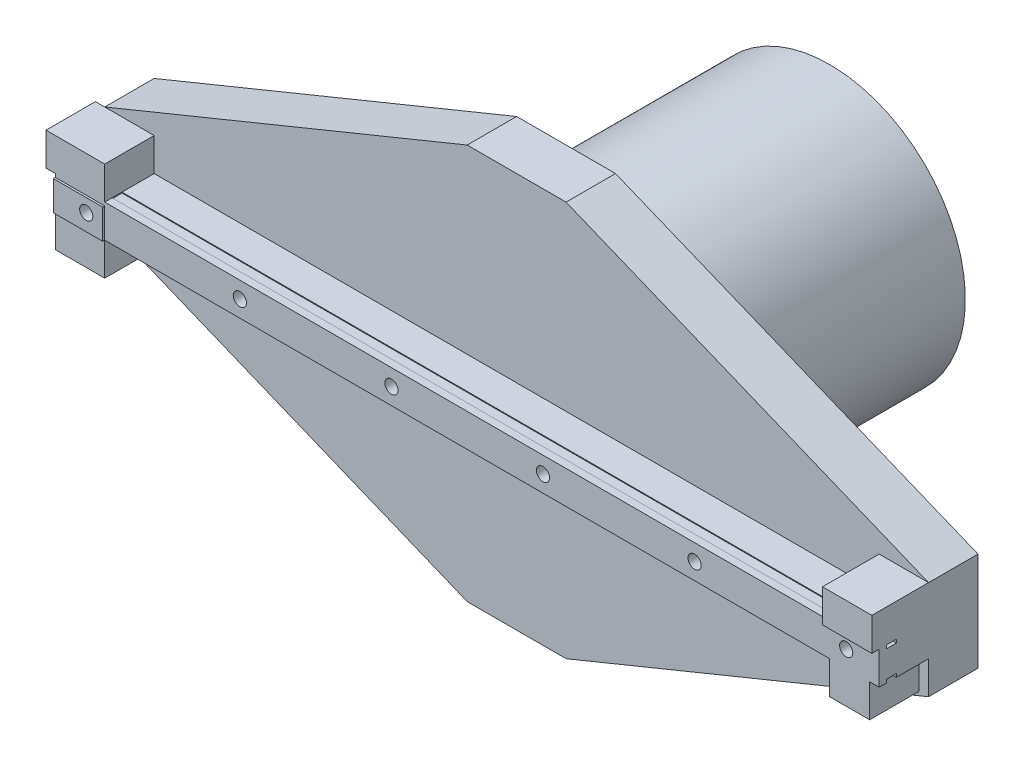
SolidWorks part; units mm, degrees
ref_plane "前视基准面" through (0, 0, 0) normal (0, 0, 1) x (1, 0, 0)
ref_plane "上视基准面" through (0, 0, 0) normal (0, 1, 0) x (1, 0, 0)
ref_plane "右视基准面" through (0, 0, 0) normal (1, 0, 0) x (0, 0, -1)
ref_plane "基准面4" through (0, -5, 0) normal (0, -1, 0) x (1, 0, 0)
sketch "草图1" plane through (0, -5, 0) normal (0, -1, 0) x (1, 0, 0)
  line L0 (-125, 95) -> (-110, 95)
  line L1 (-110, 95) -> (-110, 110.6067)
  line L2 (-110, 110.6067) -> (-125, 110.6067)
  line L3 (-125, 110.6067) -> (-125, 95)
  dimension "D1" = 15.6067
extrude "凸台-拉伸1" add sketch "草图1" against normal blind 9
sketch "草图2" plane through (-110, 0, 0) normal (1, 0, 0) x (0, 0, -1)
  line L0 (-95, 4.7491) -> (-95, -5)
  line L1 (-95, -5) -> (-104.75, -5)
  line L2 (-104.75, -5) -> (-104.75, -4)
  line L3 (-104.75, -4) -> (-107.75, -4)
  line L4 (-107.75, -4) -> (-107.75, -5)
  line L5 (-107.75, -5) -> (-110, -5)
  line L6 (-110, -5) -> (-110, 4.7491)
  line L7 (-110, 4.7491) -> (-95, 4.7491)
  dimension "D1" = 9.7491
extrude "凸台-拉伸2" add sketch "草图2" along normal blind 235
sketch "草图3" plane through (0, 4, 0) normal (0, 1, 0) x (-1, 0, 0)
  line L0 (125, 95) -> (-125, 95)
  line L1 (-125, 95) -> (-125, 110)
  line L2 (-125, 110) -> (125, 110)
  line L3 (125, 110) -> (125, 107.75)
  line L4 (125, 107.75) -> (-110, 107.75)
  line L5 (-110, 107.75) -> (-110, 104.75)
  line L6 (-110, 104.75) -> (125, 104.75)
  line L7 (125, 104.75) -> (125, 95)
extrude "凸台-拉伸3" add sketch "草图3" along normal blind 1
sketch "草图4" plane through (0, 5, 0) normal (0, 1, 0) x (-1, 0, 0)
  line L0 (-110, 112.1971) -> (-110, 95)
  line L1 (-110, 95) -> (-125, 95)
  line L2 (-125, 95) -> (-125, 112.1971)
  line L3 (-125, 112.1971) -> (-110, 112.1971)
  dimension "D1" = 17.1971
extrude "凸台-拉伸4" add sketch "草图4" along normal blind 10
ref_plane "基准面5" through (0, 4, 0) normal (0, -1, 0) x (1, 0, 0)
sketch "草图5" plane through (0, 4, 0) normal (0, -1, 0) x (1, 0, 0)
  line L0 (110, 104.75) -> (125, 104.75)
  line L1 (125, 104.75) -> (125, 107.75)
  line L2 (125, 107.75) -> (110, 107.75)
  line L3 (110, 107.75) -> (110, 104.75)
extrude "切除-拉伸1" cut sketch "草图5" against normal blind 1
sketch "草图6" plane through (0, -5, 0) normal (0, -1, 0) x (1, 0, 0)
  line L0 (122.1235, 110) -> (122.1235, 95)
  line L1 (122.1235, 95) -> (110, 95)
  line L2 (110, 95) -> (110, 110)
  line L3 (110, 110) -> (122.1235, 110)
  dimension "D1" = 12.1235
extrude "凸台-拉伸5" add sketch "草图6" along normal blind 10
sketch "草图7" plane through (0, -5, 0) normal (0, -1, 0) x (1, 0, 0)
  line L0 (-110, 110) -> (-110, 95)
  line L1 (-110, 95) -> (-125, 95)
  line L2 (-125, 95) -> (-125, 110)
  line L3 (-125, 110) -> (-110, 110)
extrude "凸台-拉伸6" add sketch "草图7" along normal blind 10
ref_plane "基准面6" through (0, -4, 0) normal (0, 1, 0) x (1, 0, 0)
sketch "草图8" plane through (0, -4, 0) normal (0, 1, 0) x (1, 0, 0)
  line L0 (-110, -104.75) -> (-125, -104.75)
  line L1 (-125, -104.75) -> (-125, -107.75)
  line L2 (-125, -107.75) -> (-110, -107.75)
  line L3 (-110, -107.75) -> (-110, -104.75)
extrude "切除-拉伸2" cut sketch "草图8" against normal blind 1
sketch "草图9" plane through (0, 5, 0) normal (0, 1, 0) x (-1, 0, 0)
  line L0 (127.8195, 110) -> (127.8195, 95)
  line L1 (127.8195, 95) -> (110, 95)
  line L2 (110, 95) -> (110, 110)
  line L3 (110, 110) -> (127.8195, 110)
  dimension "D1" = 17.8195
extrude "凸台-拉伸7" add sketch "草图9" along normal blind 10
sketch "草图10" plane through (0, 0, 95) normal (0, 0, -1) x (-1, 0, 0)
  line L0 (0, 66.1364) -> (125, 15)
  line L1 (125, 15) -> (125, -15)
  line L2 (125, -15) -> (0, -66.1364)
  line L3 (0, -66.1364) -> (-125, -15)
  line L4 (-125, -15) -> (-125, 15)
  line L5 (-125, 15) -> (0, 66.1364)
extrude "凸台-拉伸8" add sketch "草图10" along normal blind 15
ref_plane "基准面7" through (0, 0, 0) normal (0, -1, 0) x (1, 0, 0)
sketch "草图11" plane through (0, 0, 0) normal (0, -1, 0) x (1, 0, 0)
  line L0 (41.1617, 80) -> (0, 80)
  line L1 (0, 80) -> (0, 0)
  line L2 (0, 0) -> (41.1617, 0)
  line L3 (41.1617, 0) -> (41.1617, 80)
  line L4 (0, 80) -> (0, 0) construction
  dimension "D1" = 41.1617
revolve "旋转1" add sketch "草图11" angle 360 about L4
hole_wizard "Ø10.0 (10) 直径孔1" positions "3D草图1" profile "草图12" hole size "Ø10.0" standard "ANSI Metric"
sketch3d "3D草图1"
  point P0 (-41.1617, 0, 10)
sketch "草图12" plane through (-41.1617, 0, 10) normal (0, 1, 0) x (0, 0, 1)
  line L0 (0, 0) -> (0, 50)
  line L1 (0, 50) -> (5, 50)
  line L2 (5, 50) -> (5, 0)
  line L5 (5, 0) -> (0, 0)
  line L10 (0, 50) -> (-5, 50) construction
  line L11 (0, -6.35) -> (0, 107.95) construction
  dimension "孔直径" = 10
  dimension "孔深度" = 50
  dimension "导头角度" = 180
hole_wizard "Ø10.0 (10) 直径孔2" positions "3D草图2" profile "草图13" hole size "Ø10.0" standard "ANSI Metric"
sketch3d "3D草图2"
  point P0 (0, -41.1617, 10)
sketch "草图13" plane through (0, -41.1617, 10) normal (1, 0, 0) x (0, 0, -1)
  line L0 (0, 0) -> (0, 50)
  line L1 (0, 50) -> (5, 50)
  line L2 (5, 50) -> (5, 0)
  line L5 (5, 0) -> (0, 0)
  line L10 (0, 50) -> (-5, 50) construction
  line L11 (0, -6.35) -> (0, 107.95) construction
  dimension "孔直径" = 10
  dimension "孔深度" = 50
  dimension "导头角度" = 180
hole_wizard "Ø4.0 (4) 直径孔1" positions "草图15" profile "草图14" hole size "Ø4.0" standard "ANSI Metric"
sketch "草图15" plane through (0, 0, 110.6067) normal (0, 0, 1) x (1, 0, 0)
  point P0 (115, 0)
  point P1 (69, 0)
  point P2 (23, 0)
  point P3 (-23, 0)
  point P4 (-69, 0)
  point P5 (-115, 0)
sketch "草图14" plane through (115, 0, 110.6067) normal (1, 0, 0) x (0, -1, 0)
  line L0 (0, 0) -> (0, 7.5)
  line L1 (0, 7.5) -> (2, 7.5)
  line L2 (2, 7.5) -> (2, 0)
  line L5 (2, 0) -> (0, 0)
  line L10 (0, 7.5) -> (-2, 7.5) construction
  line L11 (0, -6.35) -> (0, 107.95) construction
  dimension "孔直径" = 4
  dimension "孔深度" = 7.5
  dimension "导头角度" = 180
chamfer "倒角1" distance 16.2066 angle 22.249 2 edges at (0, 66.1364, 87.5) (0, -66.1364, 87.5)
equation "\"dabanjing\" = 0.04116167m"
equation "\"xiaotai\" = 0.01719706m"
equation "\"D1@草图11\"=\"dabanjing\""
equation "\"D1@草图4\"=\"xiaotai\""
equation "\"lashen1\" = 0.01560669m"
equation "\"D1@草图1\"=\"lashen1\""
equation "\"lashen2\" = 0.00974906m"
equation "\"D1@草图2\"=\"lashen2\""
equation "\"lashen5\" = 0.01212351m"
equation "\"D1@草图6\"=\"lashen5\""
equation "\"lashen7\" = 0.01781946m"
equation "\"D1@草图9\"=\"lashen7\""
